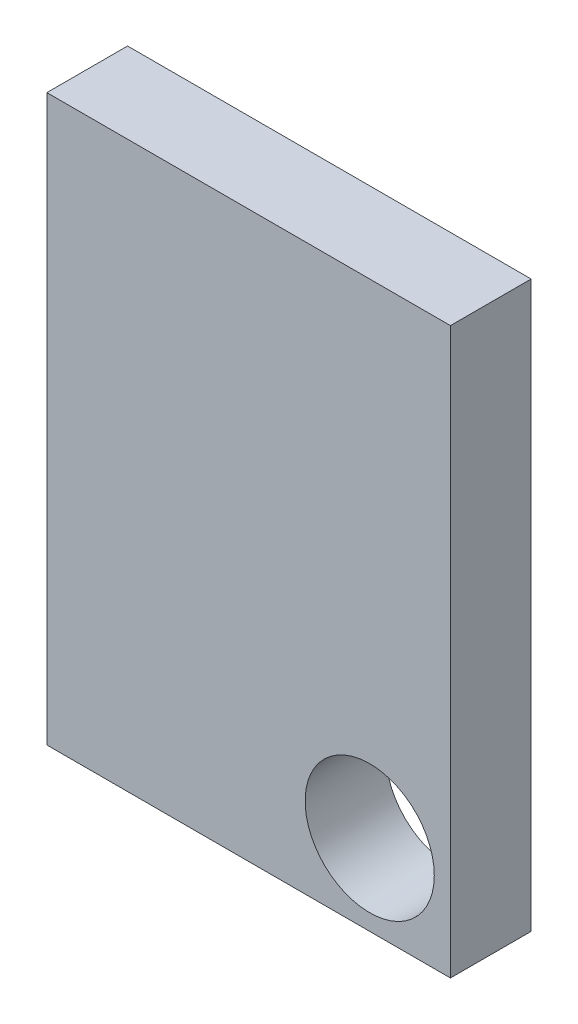
SolidWorks part; units mm, degrees
ref_plane "Front Plane" through (0, 0, 0) normal (0, 0, 1) x (1, 0, 0)
ref_plane "Top Plane" through (0, 0, 0) normal (0, 1, 0) x (1, 0, 0)
ref_plane "Right Plane" through (0, 0, 0) normal (1, 0, 0) x (0, 0, -1)
sketch "Sketch2" plane through (0, 0, 0) normal (0, 0, 1) x (1, 0, 0)
  line L1 (-12.5, -17.5) -> (12.5, -17.5)
  line L2 (-12.5, -17.5) -> (-12.5, 17.5)
  line L3 (-12.5, 17.5) -> (12.5, 17.5)
  line L4 (12.5, -17.5) -> (12.5, 17.5)
  line L5 (-12.5, -17.5) -> (12.5, 17.5) construction
  line L6 (-12.5, 17.5) -> (12.5, -17.5) construction
  point P0 (0, 0)
  dimension "D1" = 25
  dimension "D2" = 35
extrude "Boss-Extrude1" add sketch "Sketch2" along normal blind 5
sketch "Sketch6" plane through (0, 0, 5) normal (0, 0, 1) x (1, 0, 0)
  line L0 (12.5, -17.5) -> (12.5, -7.5) construction
  line L2 (12.5, -17.5) -> (12.5, 17.5) construction
  line L3 (12.5, -12.5) -> (7.5, -12.5) construction
  circle A0 centre (7.5, -12.5) radius 4
  dimension "D2" = 8
  dimension "D1" = 10
  dimension "5" = 5
extrude "Cut-Extrude2" cut sketch "Sketch6" against normal through all
